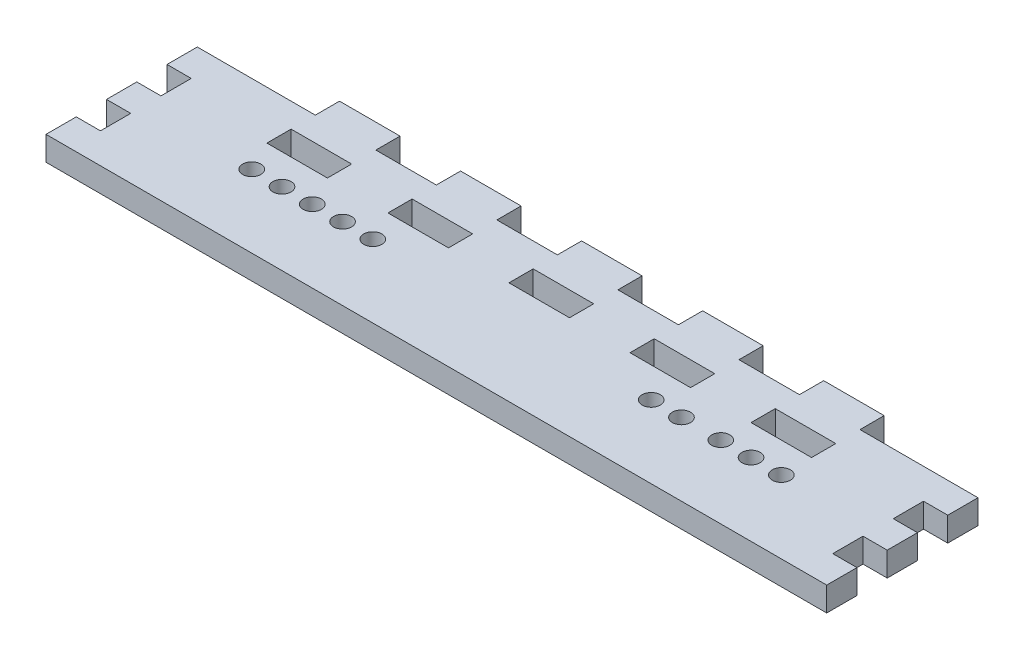
SolidWorks part; units mm, degrees
material "Maple"
ref_plane "Front Plane" through (0, 0, 0) normal (0, 0, 1) x (1, 0, 0)
ref_plane "Top Plane" through (0, 0, 0) normal (0, 1, 0) x (1, 0, 0)
ref_plane "Right Plane" through (0, 0, 0) normal (1, 0, 0) x (0, 0, -1)
sketch "Sketch1" plane through (0, 0, 0) normal (0, 1, 0) x (1, 0, 0)
  line L1 (0, 0) -> (121, 0)
  line L2 (0, 0) -> (0, -25)
  line L3 (0, -25) -> (121, -25)
  line L4 (121, 0) -> (121, -25)
  dimension "D1" = 121
  dimension "D2" = 25
extrude "Boss-Extrude1" add sketch "Sketch1" along normal blind 4
sketch "Sketch2" plane through (0, 0, 0) normal (0, -1, 0) x (-1, 0, 0)
  line L0 (0, 0) -> (0, -25) construction
  line L1 (0, -25) -> (4, -25)
  line L2 (0, -25) -> (0, -20)
  line L3 (0, -20) -> (4, -20)
  line L4 (4, -25) -> (4, -20)
  line L5 (-121, -25) -> (-125, -25)
  line L6 (-121, -25) -> (-121, -20)
  line L7 (-121, -20) -> (-125, -20)
  line L8 (-125, -25) -> (-125, -20)
  line L9 (0, -25) -> (-121, -25) construction
  dimension "D1" = 4
  dimension "D2" = 5
extrude "Boss-Extrude2" add sketch "Sketch2" against normal through all
pattern_linear "LPattern1" count 3 spacing 10 along (0, 0, -1) of "Boss-Extrude2"
sketch "Sketch3" plane through (0, 0, 0) normal (0, -1, 0) x (-1, 0, 0)
  line L0 (-60.5, -25) -> (-60.5, 0) construction
  line L1 (4, -25) -> (-125, -25) construction
  line L2 (-125, 0) -> (4, 0) construction
  line L4 (-55.5, 4) -> (-65.5, 4)
  line L5 (-55.5, 4) -> (-55.5, 0)
  line L6 (-55.5, 0) -> (-65.5, 0)
  line L7 (-65.5, 4) -> (-65.5, 0)
  line L8 (-55.5, 4) -> (-65.5, 0) construction
  line L9 (-55.5, 0) -> (-65.5, 4) construction
  point P6 (-60.5, 2)
  dimension "D1" = 4
  dimension "D2" = 10
extrude "Boss-Extrude3" add sketch "Sketch3" against normal through all
pattern_linear "LPattern2" count 3 spacing 20 along (1, 0, 0) count 3 spacing 20 along (-1, 0, 0) of "Boss-Extrude3"
sketch "Sketch4" plane through (0, 0, 0) normal (0, -1, 0) x (1, 0, 0)
  line L0 (60.5, -4) -> (60.5, 25) construction
  line L1 (15.5, 8) -> (25.5, 8)
  line L2 (15.5, 8) -> (15.5, 4)
  line L3 (15.5, 4) -> (25.5, 4)
  line L4 (25.5, 8) -> (25.5, 4)
  line L5 (35.5, 8) -> (45.5, 8)
  line L6 (35.5, 8) -> (35.5, 4)
  line L7 (35.5, 4) -> (45.5, 4)
  line L8 (45.5, 8) -> (45.5, 4)
  line L9 (55.5, 8) -> (65.5, 8)
  line L10 (55.5, 8) -> (55.5, 4)
  line L11 (55.5, 4) -> (65.5, 4)
  line L12 (65.5, 8) -> (65.5, 4)
  line L13 (75.5, 8) -> (85.5, 8)
  line L14 (75.5, 8) -> (75.5, 4)
  line L15 (75.5, 4) -> (85.5, 4)
  line L16 (85.5, 8) -> (85.5, 4)
  line L17 (95.5, 8) -> (105.5, 8)
  line L18 (95.5, 8) -> (95.5, 4)
  line L19 (95.5, 4) -> (105.5, 4)
  line L20 (105.5, 8) -> (105.5, 4)
  line L21 (55.5, -4) -> (65.5, -4) construction
  line L22 (-4, 25) -> (125, 25) construction
  dimension "D2" = 4
  dimension "D3" = 10
  dimension "D4" = 5
  dimension "D5" = 10
  dimension "D6" = 10
  dimension "D7" = 10
  dimension "D8" = 10
  dimension "D1" = 17
extrude "Cut-Extrude1" cut sketch "Sketch4" against normal through all
sketch "Sketch5" [suppressed] plane through (0, 4, 0) normal (0, 1, 0) x (1, 0, 0)
  line L0 (60.5, -25) -> (60.5, 4) construction
  line L1 (-4, -25) -> (125, -25) construction
  line L2 (55.5, 4) -> (65.5, 4) construction
  line L3 (121, -10) -> (121, -5) construction
  line L4 (54.5, -8) -> (66.5, -8)
  line L5 (54.5, -8) -> (54.5, -16)
  line L6 (54.5, -16) -> (66.5, -16)
  line L7 (66.5, -8) -> (66.5, -16)
  line L8 (54.5, -8) -> (66.5, -16) construction
  line L9 (54.5, -16) -> (66.5, -8) construction
  line L10 (0, -5) -> (0, -10) construction
  line L11 (105.5, -8) -> (95.5, -8) construction
  line L12 (55.5, -4) -> (65.5, -4) construction
  circle A0 centre (97.5, -13) radius 1.5
  circle A1 centre (102.5, -13) radius 1.5
  circle A2 centre (43, -13) radius 1.5
  circle A3 centre (38, -13) radius 1.5
  circle A4 centre (33, -13) radius 1.5
  circle A5 centre (28, -13) radius 1.5
  circle A6 centre (23, -13) radius 1.5
  circle A7 centre (18, -13) radius 1.5
  point P6 (60.5, -12)
  dimension "D4" = 3
  dimension "D5" = 3
  dimension "D1" = 8
  dimension "D2" = 12
  dimension "D6" = 5
  dimension "D8" = 18.5
  dimension "D9" = 5
  dimension "D10" = 5
  dimension "D11" = 5
  dimension "D12" = 5
  dimension "D13" = 5
  dimension "D14" = 18
  dimension "D7" = 5
  dimension "D3" = 8
extrude "Cut-Extrude2" [suppressed] cut sketch "Sketch5" against normal through all
sketch "Sketch6" plane through (0, 0, 0) normal (0, -1, 0) x (1, 0, 0)
  line L0 (45.5, 8) -> (35.5, 8) construction
  line L1 (-4, 13) -> (125, 13) construction
  line L2 (-4, 15) -> (-4, 10) construction
  line L3 (125, 10) -> (125, 15) construction
  circle A0 centre (38, 13) radius 1.5
  circle A1 centre (33, 13) radius 1.5
  circle A5 centre (28, 13) radius 1.5
  circle A6 centre (23, 13) radius 1.5
  circle A7 centre (18, 13) radius 1.5
  circle A9 centre (84, 13) radius 1.5
  circle A10 centre (89, 13) radius 1.5
  circle A11 centre (95.5, 13) radius 1.5
  circle A12 centre (100.5, 13) radius 1.5
  circle A13 centre (105.5, 13) radius 1.5
  dimension "D6" = 5
  dimension "D9" = 5
  dimension "D10" = 5
  dimension "D11" = 5
  dimension "D1" = 3
  dimension "D2" = 5
  dimension "D3" = 5
  dimension "D4" = 5
  dimension "D5" = 5
  dimension "D12" = 19.5
  dimension "D13" = 36
  dimension "D7" = 22
extrude "Cut-Extrude3" cut sketch "Sketch6" against normal through all
equation "\"D5@Sketch5\"=\"D4@Sketch5\""
equation "\"D10@Sketch5\"=\"D9@Sketch5\""
equation "\"D11@Sketch5\"=\"D9@Sketch5\""
equation "\"D12@Sketch5\"=\"D9@Sketch5\""
equation "\"D13@Sketch5\"=\"D9@Sketch5\""
equation "\"D6@Sketch4\"=\"D5@Sketch4\""
equation "\"D7@Sketch4\"=\"D5@Sketch4\""
equation "\"D8@Sketch4\"=\"D5@Sketch4\""
equation "\"D5@Sketch6\"=\"D3@Sketch6\""
equation "\"D4@Sketch6\"=\"D3@Sketch6\""
equation "\"D6@Sketch6\"=\"D3@Sketch6\""
equation "\"D9@Sketch6\"=\"D3@Sketch6\""
equation "\"D10@Sketch6\"=\"D3@Sketch6\""
equation "\"D11@Sketch6\"=\"D3@Sketch6\""
